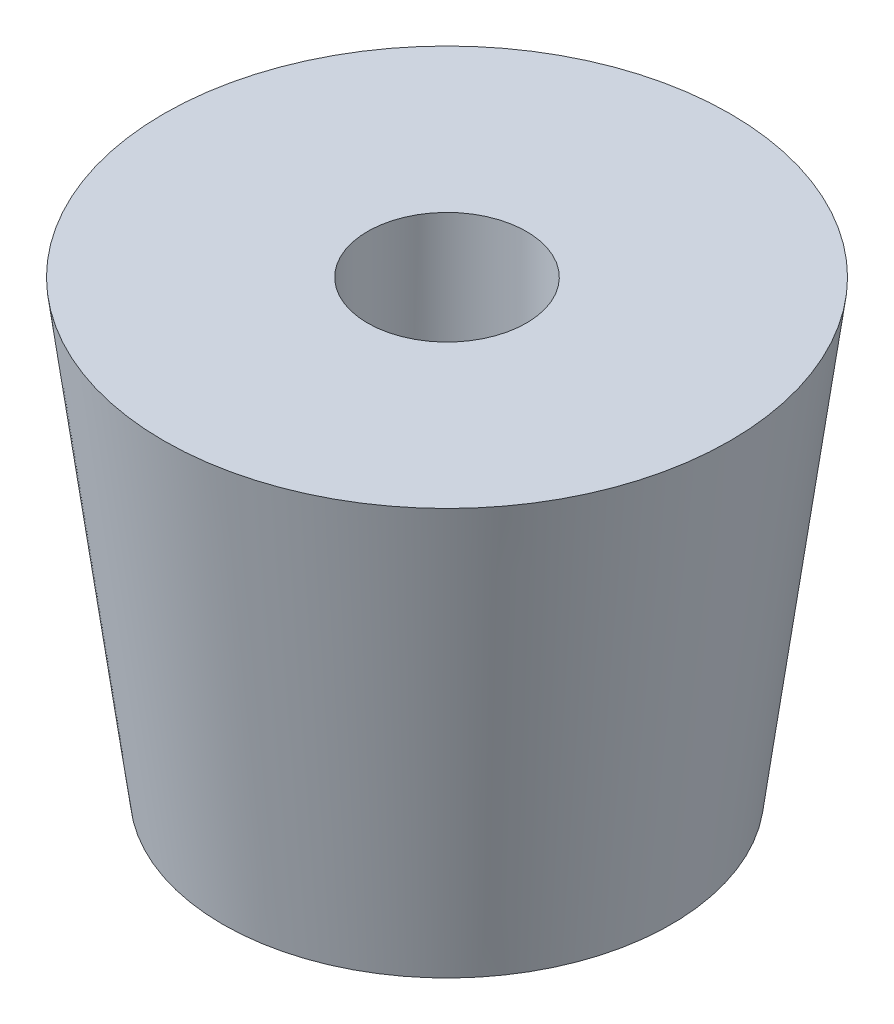
SolidWorks part; units mm, degrees
ref_plane "Front" through (0, 0, 0) normal (0, 0, 1) x (1, 0, 0)
ref_plane "Top" through (0, 0, 0) normal (0, 1, 0) x (1, 0, 0)
ref_plane "Right" through (0, 0, 0) normal (1, 0, 0) x (0, 0, -1)
sketch "Sketch1" plane through (0, 0, 0) normal (0, 1, 0) x (1, 0, 0)
  circle A0 centre (0, 0) radius 6.35
  dimension "D1" = 12.7
extrude "Boss-Extrude1" add sketch "Sketch1" along normal blind 12.7 draft 7.5 draft outward yes
sketch "Sketch2" plane through (0, 0, 0) normal (0, -1, 0) x (1, 0, 0)
  circle A0 centre (0, 0) radius 3.5
  dimension "D1" = 7
extrude "Cut-Extrude1" cut sketch "Sketch2" against normal blind 8.89
sketch "Sketch3" plane through (0, 12.7, 0) normal (0, 1, 0) x (1, 0, 0)
  circle A0 centre (0, 0) radius 2.25
  dimension "D1" = 4.5
extrude "Cut-Extrude2" cut sketch "Sketch3" against normal through all
